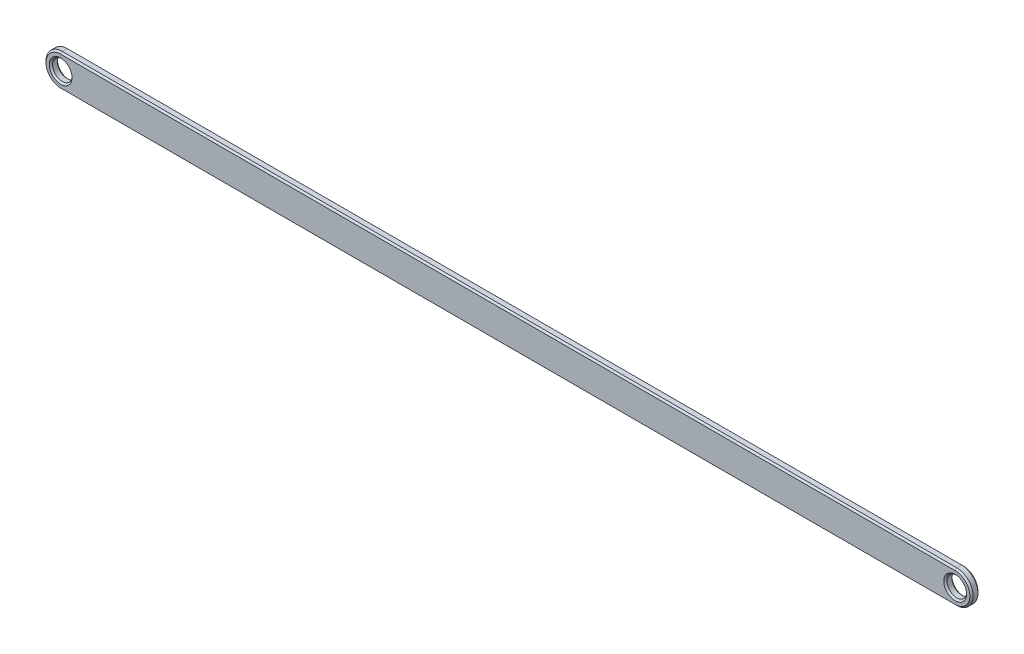
SolidWorks part; units mm, degrees
ref_plane "Front Plane" through (0, 0, 0) normal (0, 0, 1) x (1, 0, 0)
ref_plane "Top Plane" through (0, 0, 0) normal (0, 1, 0) x (1, 0, 0)
ref_plane "Right Plane" through (0, 0, 0) normal (1, 0, 0) x (0, 0, -1)
sketch "Sketch1" plane through (0, 0, 0) normal (0, 0, 1) x (1, 0, 0)
  line L0 (0, 157.4916) -> (0, -223.2358) construction
  line L1 (1372.5, -50) -> (-1372.5, -50)
  line L3 (1372.5, 50) -> (-1372.5, 50)
  line L4 (-1372.5, 0) -> (1372.5, 0) construction
  arc A0 (-1372.5, 50) -> (-1372.5, -50) centre (-1372.5, 0) ccw
  circle A1 centre (-1372.5, 0) radius 30
  arc A2 (1372.5, 50) -> (1372.5, -50) centre (1372.5, 0) cw
  circle A3 centre (1372.5, 0) radius 30
  point P0 (0, 0)
  dimension "D1" = 60
  dimension "D2" = 20
  dimension "D3" = 2745
extrude "Boss-Extrude1" add sketch "Sketch1" along normal blind 25
chamfer "Chamfer1" distance 5 angle 45 12 edges at (1342.5, 0, 0) (-1342.5, 0, 0) (0, -50, 0) (1422.5, 0, 0) (0, 50, 0) (-1422.5, 0, 0) (1342.5, 0, 25) (0, 50, 25) (1422.5, 0, 25) (0, -50, 25) (-1422.5, 0, 25) (-1342.5, 0, 25)
equation "\"length\"= 2745"
equation "\"D3@Sketch1\"=\"length\""
